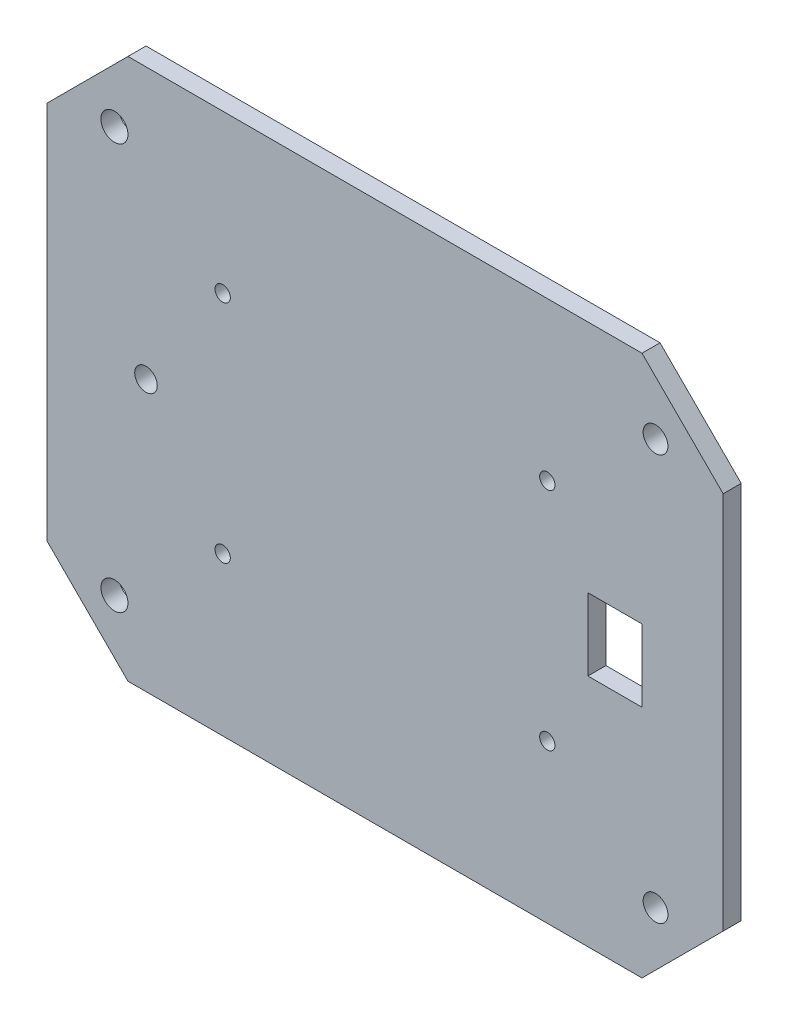
SolidWorks part; units mm, degrees
ref_plane "Спереди" through (0, 0, 0) normal (0, 0, 1) x (1, 0, 0)
ref_plane "Сверху" through (0, 0, 0) normal (0, 1, 0) x (1, 0, 0)
ref_plane "Справа" through (0, 0, 0) normal (1, 0, 0) x (0, 0, -1)
other "Configuration Table"
sketch "Эскиз1" plane through (0, 0, 0) normal (0, 0, 1) x (1, 0, 0)
  line L0 (-57, -60) -> (57, -60)
  line L1 (57, -60) -> (75, -42)
  line L2 (75, -42) -> (75, 42)
  line L3 (75, 42) -> (57, 60)
  line L4 (57, 60) -> (-57, 60)
  line L5 (-57, 60) -> (-75, 42)
  line L6 (-75, 42) -> (-75, -42)
  line L7 (-75, -42) -> (-57, -60)
  line L9 (45, -8) -> (57, -8)
  line L10 (45, -8) -> (45, 8)
  line L11 (45, 8) -> (57, 8)
  line L12 (57, -8) -> (57, 8)
  circle A0 centre (-60, -45) radius 3
  circle A1 centre (-60, 45) radius 3
  circle A2 centre (60, -45) radius 2.75
  circle A3 centre (60, 45) radius 2.75
  circle A4 centre (-36, -25) radius 1.7
  circle A5 centre (-36, 25) radius 1.7
  circle A6 centre (36, -25) radius 1.7
  circle A7 centre (36, 25) radius 1.7
  circle A8 centre (-53, 0) radius 2.5
extrude "01_Ceiling_M5" add sketch "Эскиз1" along normal blind 4
